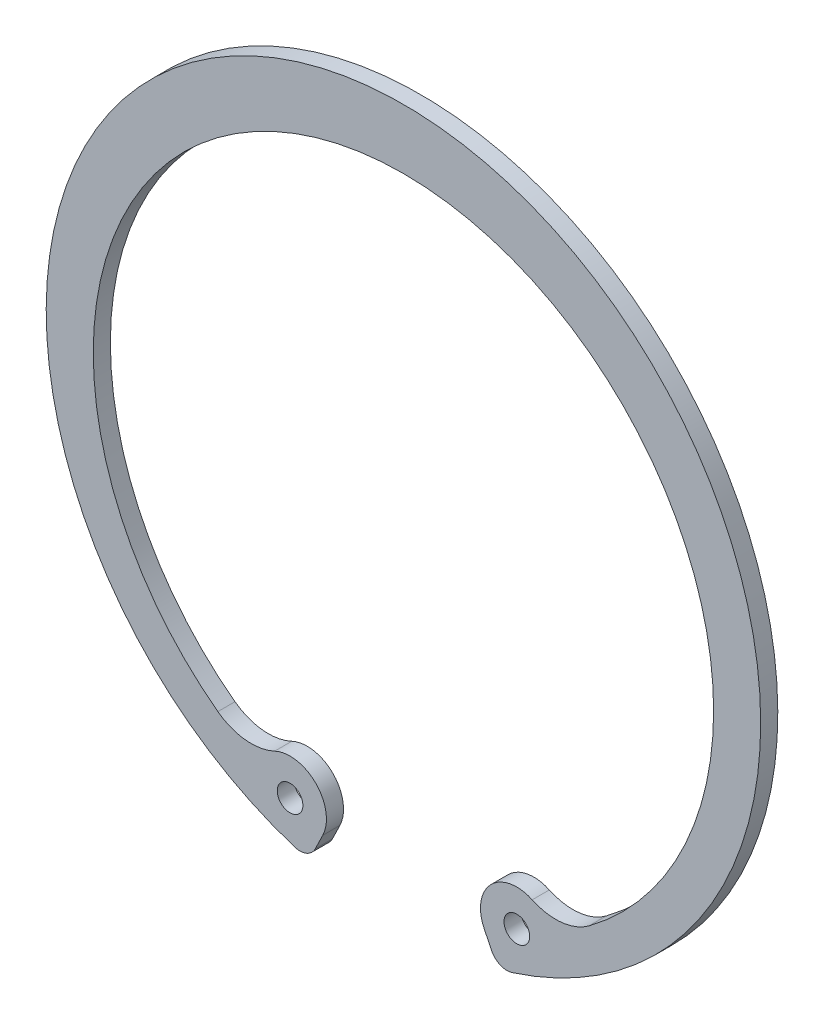
SolidWorks part; units mm, degrees
material "Сталь 45 ГОСТ 1050-88"
ref_plane "Спереди" through (0, 0, 0) normal (0, 0, 1) x (1, 0, 0)
ref_plane "Сверху" through (0, 0, 0) normal (0, 1, 0) x (1, 0, 0)
ref_plane "Справа" through (0, 0, 0) normal (1, 0, 0) x (0, 0, -1)
sketch "Эскиз1" plane through (0, 0, 0) normal (0, 0, 1) x (1, 0, 0)
  line L0 (0, 0) -> (0, -5.2439) construction
  line L1 (-10.3017, -38.7376) -> (-9.4275, -36.9388)
  line L2 (10.3017, -38.7376) -> (9.4275, -36.9388)
  arc A0 (12.7093, -39.7685) -> (-12.7093, -39.7685) centre (0, 0) ccw
  circle A2 centre (0, 0) radius 31 construction
  circle A3 centre (0, 0) radius 40 construction
  circle A4 centre (-13.25, -35.0812) radius 4.25 construction
  circle A5 centre (13.25, -35.0812) radius 4.25 construction
  arc A6 (-15.0475, -31.23) -> (-9.4275, -36.9388) centre (-13.25, -35.0812) cw
  arc A7 (-15.0475, -31.23) -> (-21.6849, -30.5487) centre (-17.7966, -25.34) cw
  arc A8 (-12.7093, -39.7685) -> (-10.3017, -38.7376) centre (-12.1005, -37.8634) ccw
  circle A9 centre (-13.25, -35.0812) radius 1.5
  arc A10 (12.7093, -39.7685) -> (10.3017, -38.7376) centre (12.1005, -37.8634) cw
  circle A11 centre (13.25, -35.0812) radius 1.5
  arc A12 (15.0475, -31.23) -> (9.4275, -36.9388) centre (13.25, -35.0812) ccw
  arc A13 (15.0475, -31.23) -> (21.6849, -30.5487) centre (17.7966, -25.34) ccw
  arc A14 (21.6849, -30.5487) -> (-21.6849, -30.5487) centre (0, -1.5) ccw
  dimension "d2" = 83.5
  dimension "d3" = 72.5
  dimension "D" = 62
  dimension "Dval" = 80
  dimension "a" = 8.5
  dimension "r1" = 6.5
  dimension "r2" = 2
  dimension "d4" = 3
  dimension "b" = 7
  dimension "l" = 18
  dimension "z" = 2
extrude "Бобышка8-165" add sketch "Эскиз1" along normal blind 2
sketch "Эскиз170-320" [suppressed] plane through (0, 0, 0) normal (0, 0, 1) x (1, 0, 0)
  line L0 (0, 0) -> (0, -150) construction
  line L1 (-19.4384, -152.7683) -> (-18, -141.6414)
  line L2 (19.4384, -152.7683) -> (18, -141.6414)
  line L3 (-24.9033, -151.9731) -> (-24.4198, -148.2325) construction
  line L4 (-22.4598, -146.7213) -> (-18.7192, -147.2048) construction
  arc A0 (19.4384, -152.7683) -> (-19.4384, -152.7683) centre (0, 0) ccw
  arc A1 (18, -141.6414) -> (-18, -141.6414) centre (0, -2.4) ccw
  circle A2 centre (0, 0) radius 150 construction
  circle A3 centre (0, 0) radius 150 construction
  circle A4 centre (-24.1954, -146.4969) radius 1.75
  circle A5 centre (24.1954, -146.4969) radius 1.75
  dimension "Dotv" = 300
  dimension "d2" = 175
  dimension "d3" = 156.7
  dimension "d4" = 3
  dimension "b" = 12.2
  dimension "l" = 28
extrude "Бобышка170-320" [suppressed] add sketch "Эскиз170-320" along normal blind 3 separate body
